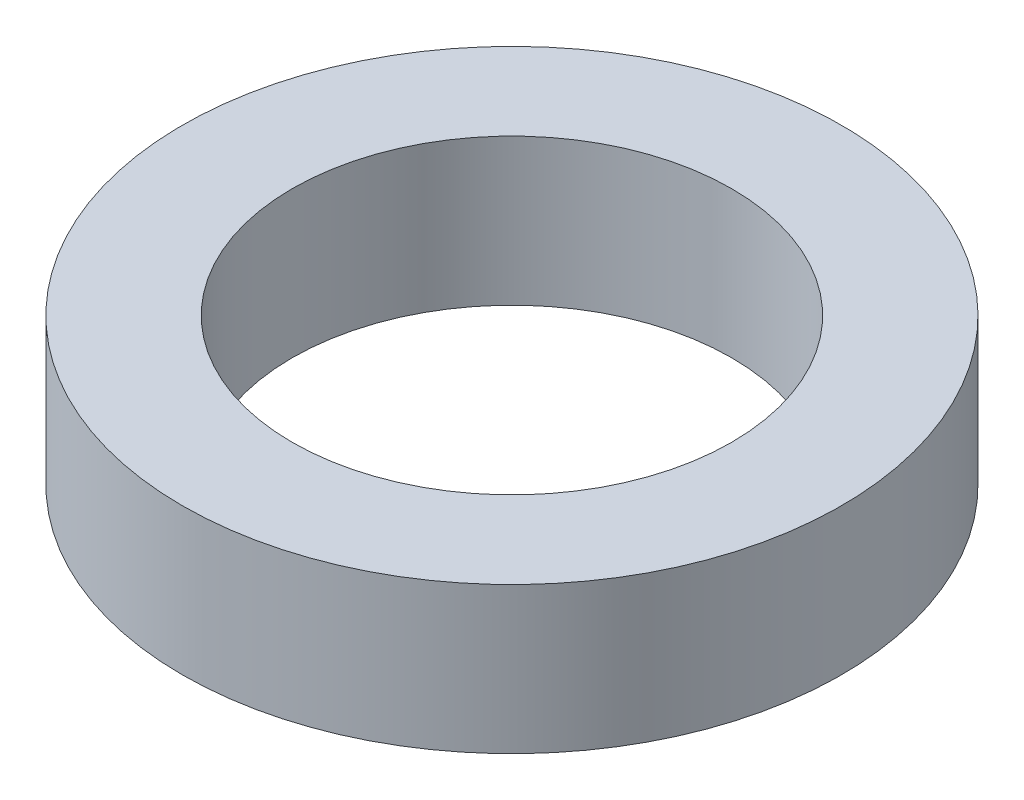
SolidWorks part; units mm, degrees
ref_plane "Ön Düzlem" through (0, 0, 0) normal (0, 0, 1) x (1, 0, 0)
ref_plane "Üst Düzlem" through (0, 0, 0) normal (0, 1, 0) x (1, 0, 0)
ref_plane "Sağ Düzlem" through (0, 0, 0) normal (1, 0, 0) x (0, 0, -1)
sketch "Sketch1" plane through (0, 0, 0) normal (0, 1, 0) x (1, 0, 0)
  circle A0 centre (0, 0) radius 6
  circle A1 centre (0, 0) radius 9
  dimension "D1" = 12
  dimension "D2" = 18
extrude "Boss-Extrude1" add sketch "Sketch1" along normal blind 4
